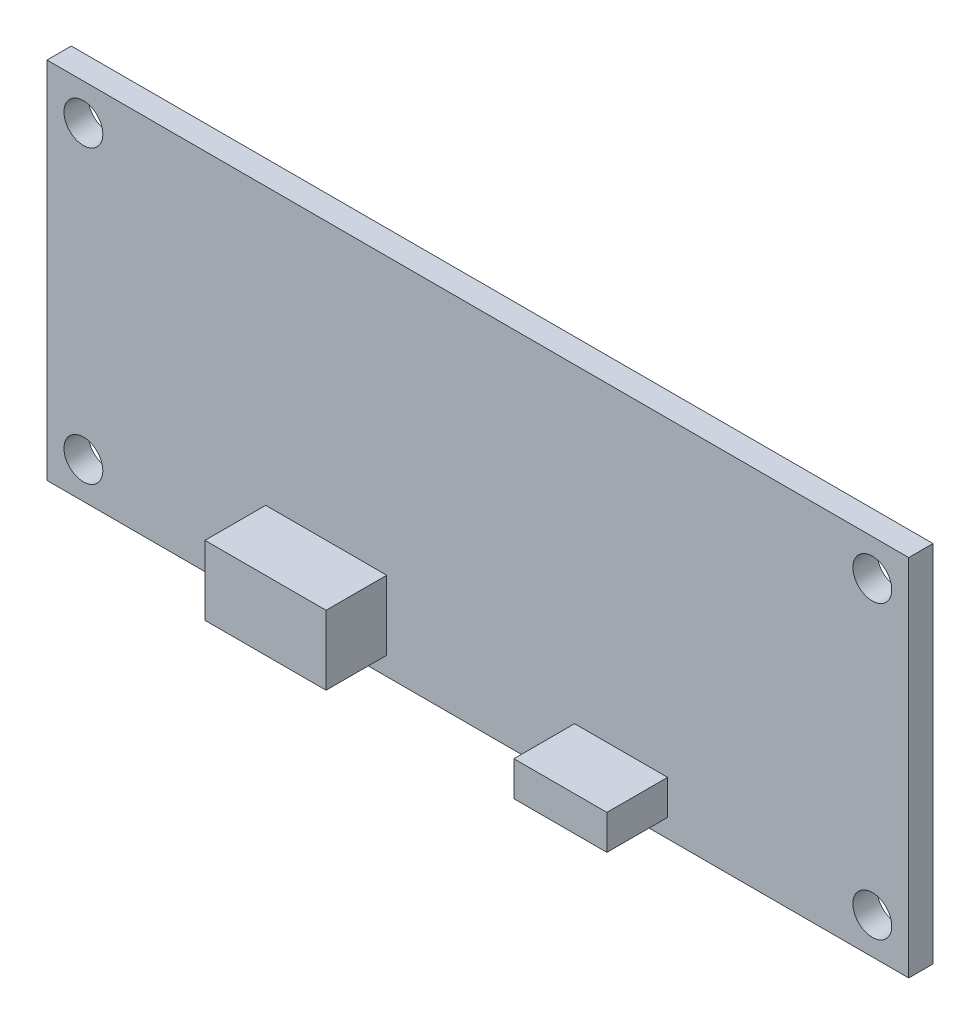
SolidWorks part; units mm, degrees
ref_plane "Front" through (0, 0, 0) normal (0, 0, 1) x (1, 0, 0)
ref_plane "Top" through (0, 0, 0) normal (0, 1, 0) x (1, 0, 0)
ref_plane "Right" through (0, 0, 0) normal (1, 0, 0) x (0, 0, -1)
sketch "草图1" plane through (0, 0, 0) normal (0, 0, 1) x (1, 0, 0)
  line L1 (0, 0) -> (71, 0)
  line L2 (0, 0) -> (0, 30)
  line L3 (0, 30) -> (71, 30)
  line L4 (71, 0) -> (71, 30)
  circle A0 centre (3, 27) radius 1.6
  circle A1 centre (68, 3) radius 1.6
  circle A2 centre (3, 3) radius 1.6
  circle A3 centre (68, 27) radius 1.6
  dimension "D3" = 3
  dimension "D4" = 3
  dimension "D5" = 3
  dimension "D6" = 3
  dimension "D1" = 30
  dimension "D2" = 71
extrude "凸台-拉伸1" add sketch "草图1" along normal blind 2
sketch "草图2" plane through (0, 0, 2) normal (0, 0, 1) x (1, 0, 0)
  line L1 (18.0169, 7.2354) -> (27.9925, 7.2354)
  line L2 (18.0169, 7.2354) -> (18.0169, 1.5277)
  line L3 (18.0169, 1.5277) -> (27.9925, 1.5277)
  line L4 (27.9925, 7.2354) -> (27.9925, 1.5277)
  line L5 (43.4703, 4.3816) -> (51.132, 4.3816)
  line L6 (43.4703, 4.3816) -> (43.4703, 1.5277)
  line L7 (43.4703, 1.5277) -> (51.132, 1.5277)
  line L8 (51.132, 4.3816) -> (51.132, 1.5277)
extrude "凸台-拉伸2" add sketch "草图2" along normal blind 5
